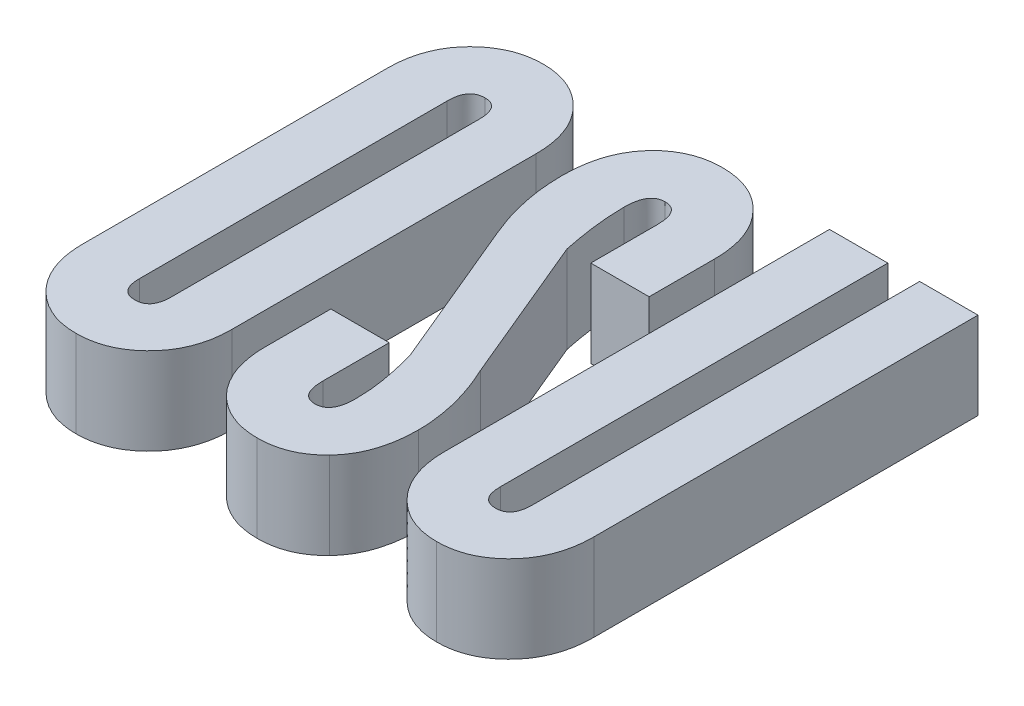
SolidWorks part; units mm, degrees
ref_plane "Front Plane" through (0, 0, 0) normal (0, 0, 1) x (1, 0, 0)
ref_plane "Top Plane" through (0, 0, 0) normal (0, 1, 0) x (1, 0, 0)
ref_plane "Right Plane" through (0, 0, 0) normal (1, 0, 0) x (0, 0, -1)
sketch "Sketch1" plane through (0, 0, 0) normal (0, 1, 0) x (1, 0, 0)
  text T0 "OSU" font "Cactus" height in points 48
extrude "Boss-Extrude1" add sketch "Sketch1" along normal blind 3.302
